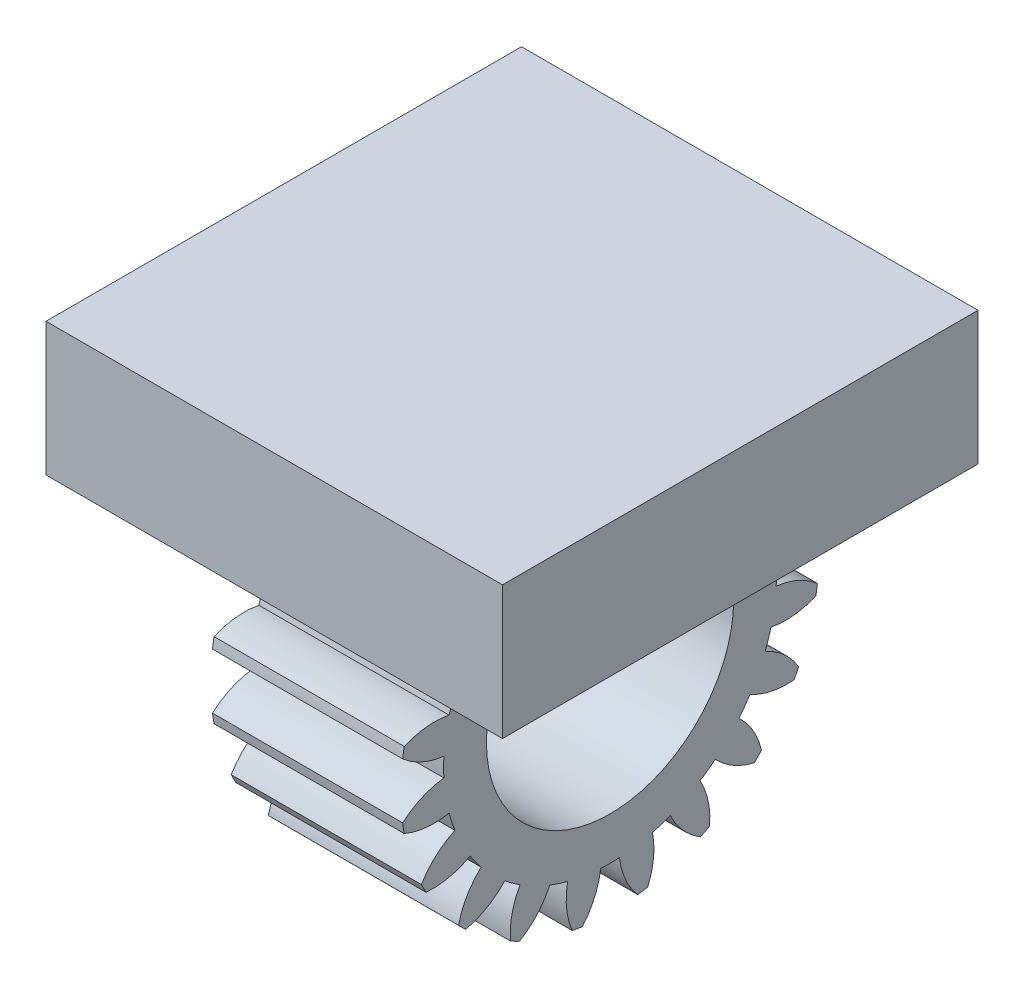
SolidWorks part; units mm, degrees
ref_plane "Front Plane" through (0, 0, 0) normal (0, 0, 1) x (1, 0, 0)
ref_plane "Top Plane" through (0, 0, 0) normal (0, 1, 0) x (1, 0, 0)
ref_plane "Right Plane" through (0, 0, 0) normal (1, 0, 0) x (0, 0, -1)
ref_plane "Plane1" through (30.4852, 0, 0) normal (1, 0, 0) x (0, 0, -1)
sketch "Sketch1" plane through (30.4852, 0, 0) normal (1, 0, 0) x (0, 0, -1)
  circle A0 centre (-23.9245, -5.8647) radius 13
  arc A1 (-45.7308, -2.952) -> (-41.3957, -4.8786) centre (-40.4605, 3.0666) ccw
  arc A2 (-41.3957, -4.8786) -> (-41.3957, -6.8509) centre (-23.9245, -5.8647) ccw
  arc A3 (-41.3957, -6.8509) -> (-45.7308, -8.7774) centre (-40.4605, -14.7961) ccw
  arc A4 (-45.7308, -8.7774) -> (-45.5636, -9.8331) centre (-23.9245, -5.8647) ccw
  arc A5 (-45.5636, -9.8331) -> (-40.8453, -10.3257) centre (-42.4111, -2.4805) ccw
  arc A6 (-40.8453, -10.3257) -> (-40.2358, -12.2015) centre (-23.9245, -5.8647) ccw
  arc A7 (-40.2358, -12.2015) -> (-43.7635, -15.3734) centre (-36.8912, -19.4688) ccw
  arc A8 (-43.7635, -15.3734) -> (-43.2782, -16.3258) centre (-23.9245, -5.8647) ccw
  arc A9 (-43.2782, -16.3258) -> (-38.6386, -15.3362) centre (-42.5521, -8.3588) ccw
  arc A10 (-38.6386, -15.3362) -> (-37.4793, -16.9319) centre (-23.9245, -5.8647) ccw
  arc A11 (-37.4793, -16.9319) -> (-39.8541, -21.0386) centre (-32.0527, -22.81) ccw
  arc A12 (-39.8541, -21.0386) -> (-39.0983, -21.7944) centre (-23.9245, -5.8647) ccw
  arc A13 (-39.0983, -21.7944) -> (-34.9916, -19.4196) centre (-40.8697, -13.993) ccw
  arc A14 (-34.9916, -19.4196) -> (-33.396, -20.5789) centre (-23.9245, -5.8647) ccw
  arc A15 (-33.396, -20.5789) -> (-34.3855, -25.2185) centre (-26.4185, -24.4924) ccw
  arc A16 (-34.3855, -25.2185) -> (-33.4331, -25.7037) centre (-23.9245, -5.8647) ccw
  arc A17 (-33.4331, -25.7037) -> (-30.2613, -22.1761) centre (-37.5286, -18.8315) ccw
  arc A18 (-30.2613, -22.1761) -> (-28.3855, -22.7856) centre (-23.9245, -5.8647) ccw
  arc A19 (-28.3855, -22.7856) -> (-27.8929, -27.5039) centre (-20.5402, -24.3514) ccw
  arc A20 (-27.8929, -27.5039) -> (-26.8372, -27.6711) centre (-23.9245, -5.8647) ccw
  arc A21 (-26.8372, -27.6711) -> (-24.9107, -23.3359) centre (-32.8558, -22.4008) ccw
  arc A22 (-24.9107, -23.3359) -> (-22.9383, -23.3359) centre (-23.9245, -5.8647) ccw
  arc A23 (-22.9383, -23.3359) -> (-21.0118, -27.6711) centre (-14.9932, -22.4008) ccw
  arc A24 (-21.0118, -27.6711) -> (-19.9561, -27.5039) centre (-23.9245, -5.8647) ccw
  arc A25 (-19.9561, -27.5039) -> (-19.4635, -22.7856) centre (-27.3088, -24.3514) ccw
  arc A26 (-19.4635, -22.7856) -> (-17.5877, -22.1761) centre (-23.9245, -5.8647) ccw
  arc A27 (-17.5877, -22.1761) -> (-14.4158, -25.7037) centre (-10.3204, -18.8315) ccw
  arc A28 (-14.4158, -25.7037) -> (-13.4635, -25.2185) centre (-23.9245, -5.8647) ccw
  arc A29 (-13.4635, -25.2185) -> (-14.453, -20.5789) centre (-21.4304, -24.4924) ccw
  arc A30 (-14.453, -20.5789) -> (-12.8573, -19.4196) centre (-23.9245, -5.8647) ccw
  arc A31 (-12.8573, -19.4196) -> (-8.7506, -21.7944) centre (-6.9793, -13.993) ccw
  arc A32 (-8.7506, -21.7944) -> (-7.9948, -21.0386) centre (-23.9245, -5.8647) ccw
  arc A33 (-7.9948, -21.0386) -> (-10.3696, -16.9319) centre (-15.7963, -22.81) ccw
  arc A34 (-10.3696, -16.9319) -> (-9.2103, -15.3362) centre (-23.9245, -5.8647) ccw
  arc A35 (-9.2103, -15.3362) -> (-4.5707, -16.3258) centre (-5.2968, -8.3588) ccw
  arc A36 (-4.5707, -16.3258) -> (-4.0855, -15.3734) centre (-23.9245, -5.8647) ccw
  arc A37 (-4.0855, -15.3734) -> (-7.6131, -12.2015) centre (-10.9577, -19.4688) ccw
  arc A38 (-7.6131, -12.2015) -> (-7.0036, -10.3257) centre (-23.9245, -5.8647) ccw
  arc A39 (-7.0036, -10.3257) -> (-2.2854, -9.8331) centre (-5.4378, -2.4805) ccw
  arc A40 (-2.2854, -9.8331) -> (-2.1181, -8.7774) centre (-23.9245, -5.8647) ccw
  arc A41 (-2.1181, -8.7774) -> (-6.4533, -6.8509) centre (-7.3884, -14.7961) ccw
  arc A42 (-6.4533, -6.8509) -> (-6.4533, -4.8786) centre (-23.9245, -5.8647) ccw
  arc A43 (-6.4533, -4.8786) -> (-2.1181, -2.952) centre (-7.3884, 3.0666) ccw
  arc A44 (-2.1181, -2.952) -> (-2.2854, -1.8963) centre (-23.9245, -5.8647) ccw
  arc A45 (-2.2854, -1.8963) -> (-7.0036, -1.4037) centre (-5.4378, -9.249) ccw
  arc A46 (-7.0036, -1.4037) -> (-7.6131, 0.4721) centre (-23.9245, -5.8647) ccw
  arc A47 (-7.6131, 0.4721) -> (-4.0855, 3.6439) centre (-10.9577, 7.7394) ccw
  arc A48 (-4.0855, 3.6439) -> (-4.5707, 4.5963) centre (-23.9245, -5.8647) ccw
  arc A49 (-4.5707, 4.5963) -> (-9.2103, 3.6067) centre (-5.2968, -3.3707) ccw
  arc A50 (-9.2103, 3.6067) -> (-10.3696, 5.2024) centre (-23.9245, -5.8647) ccw
  arc A51 (-10.3696, 5.2024) -> (-7.9948, 9.3091) centre (-15.7963, 11.0805) ccw
  arc A52 (-7.9948, 9.3091) -> (-8.7506, 10.0649) centre (-23.9245, -5.8647) ccw
  arc A53 (-8.7506, 10.0649) -> (-12.8573, 7.6901) centre (-6.9793, 2.2635) ccw
  arc A54 (-12.8573, 7.6901) -> (-14.453, 8.8494) centre (-23.9245, -5.8647) ccw
  arc A55 (-14.453, 8.8494) -> (-13.4635, 13.489) centre (-21.4304, 12.7629) ccw
  arc A56 (-13.4635, 13.489) -> (-14.4158, 13.9742) centre (-23.9245, -5.8647) ccw
  arc A57 (-14.4158, 13.9742) -> (-17.5877, 10.4466) centre (-10.3204, 7.102) ccw
  arc A58 (-17.5877, 10.4466) -> (-19.4635, 11.0561) centre (-23.9245, -5.8647) ccw
  arc A59 (-19.4635, 11.0561) -> (-19.9561, 15.7744) centre (-27.3088, 12.6219) ccw
  arc A60 (-19.9561, 15.7744) -> (-21.0118, 15.9416) centre (-23.9245, -5.8647) ccw
  arc A61 (-21.0118, 15.9416) -> (-22.9383, 11.6065) centre (-14.9932, 10.6713) ccw
  arc A62 (-22.9383, 11.6065) -> (-24.9107, 11.6065) centre (-23.9245, -5.8647) ccw
  arc A63 (-24.9107, 11.6065) -> (-26.8372, 15.9416) centre (-32.8558, 10.6713) ccw
  arc A64 (-26.8372, 15.9416) -> (-27.8929, 15.7744) centre (-23.9245, -5.8647) ccw
  arc A65 (-27.8929, 15.7744) -> (-28.3855, 11.0561) centre (-20.5402, 12.6219) ccw
  arc A66 (-28.3855, 11.0561) -> (-30.2613, 10.4466) centre (-23.9245, -5.8647) ccw
  arc A67 (-30.2613, 10.4466) -> (-33.4331, 13.9742) centre (-37.5286, 7.102) ccw
  arc A68 (-33.4331, 13.9742) -> (-34.3855, 13.489) centre (-23.9245, -5.8647) ccw
  arc A69 (-34.3855, 13.489) -> (-33.396, 8.8494) centre (-26.4185, 12.7629) ccw
  arc A70 (-33.396, 8.8494) -> (-34.9916, 7.6901) centre (-23.9245, -5.8647) ccw
  arc A71 (-34.9916, 7.6901) -> (-39.0983, 10.0649) centre (-40.8697, 2.2635) ccw
  arc A72 (-39.0983, 10.0649) -> (-39.8541, 9.3091) centre (-23.9245, -5.8647) ccw
  arc A73 (-39.8541, 9.3091) -> (-37.4793, 5.2024) centre (-32.0527, 11.0805) ccw
  arc A74 (-37.4793, 5.2024) -> (-38.6386, 3.6067) centre (-23.9245, -5.8647) ccw
  arc A75 (-38.6386, 3.6067) -> (-43.2782, 4.5963) centre (-42.5521, -3.3707) ccw
  arc A76 (-43.2782, 4.5963) -> (-43.7635, 3.6439) centre (-23.9245, -5.8647) ccw
  arc A77 (-43.7635, 3.6439) -> (-40.2358, 0.4721) centre (-36.8912, 7.7394) ccw
  arc A78 (-40.2358, 0.4721) -> (-40.8453, -1.4037) centre (-23.9245, -5.8647) ccw
  arc A79 (-40.8453, -1.4037) -> (-45.5636, -1.8963) centre (-42.4111, -9.249) ccw
  arc A80 (-45.5636, -1.8963) -> (-45.7308, -2.952) centre (-23.9245, -5.8647) ccw
extrude "Boss-Extrude1" add sketch "Sketch1" against normal blind 20
sketch "Sketch2" plane through (30.4852, 0, 0) normal (1, 0, 0) x (0, 0, -1)
  line L1 (-49.2335, 21.6532) -> (0.7665, 21.6532)
  line L2 (-49.2335, 21.6532) -> (-49.2335, 7.6532)
  line L3 (-49.2335, 7.6532) -> (0.7665, 7.6532)
  line L4 (0.7665, 21.6532) -> (0.7665, 7.6532)
  dimension "D1" = 50
  dimension "D2" = 14
extrude "Boss-Extrude2" add sketch "Sketch2" along normal blind 14 and the other way blind 34
